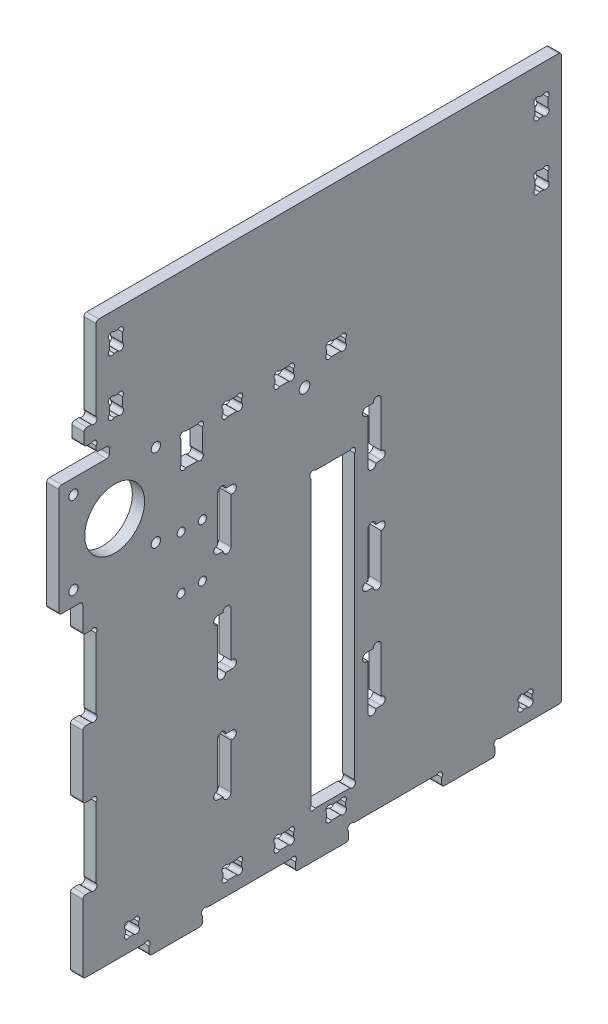
SolidWorks part; units mm, degrees
material "Acrylic (Medium-high impact)"
ref_plane "Front Plane" through (0, 0, 0) normal (0, 0, 1) x (1, 0, 0)
ref_plane "Top Plane" through (0, 0, 0) normal (0, 1, 0) x (1, 0, 0)
ref_plane "Right Plane" through (0, 0, 0) normal (1, 0, 0) x (0, 0, -1)
sketch "Sketch21" plane through (0, 0, 0) normal (1, 0, 0) x (0, 0, -1)
  line L0 (-68, 106) -> (107, 106)
  line L1 (107, 106) -> (107, -106)
  line L2 (107, -106) -> (82, -106)
  line L3 (-45.5, 53.5) -> (-76.5, 53.5) construction
  line L4 (-76.5, 53.5) -> (-76.5, 22.5) construction
  line L5 (-76.5, 22.5) -> (-45.5, 22.5) construction
  line L6 (-13.25, -101) -> (18.75, -101) construction
  line L7 (-20.25, -101) -> (-20.25, -96)
  line L8 (-82, 59) -> (-63, 59)
  line L9 (-48, -106) -> (-48, -111)
  line L10 (-68, 73) -> (-68, 106)
  line L11 (-68, 63) -> (-68, 67)
  line L12 (-73, -106) -> (-48, -106)
  line L13 (-48, -111) -> (-28, -111)
  line L14 (-13.25, -96) -> (-20.25, -96)
  line L15 (-13.25, -101) -> (-13.25, -96)
  line L16 (-13.25, -101) -> (-20.25, -101)
  line L17 (18.75, -101) -> (25.75, -101)
  line L18 (-45.5, 22.5) -> (-45.5, 53.5) construction
  line L19 (-45.5, 53.5) -> (-76.5, 22.5) construction
  line L20 (-57, -96) -> (-52, -96)
  line L21 (-57, -96) -> (-57, -101)
  line L22 (-57, -101) -> (-52, -101)
  line L23 (-52, -96) -> (-52, -101)
  line L24 (91, -96) -> (96, -96)
  line L25 (91, -96) -> (91, -101)
  line L26 (-28, -111) -> (-28, -106)
  line L27 (82, -106) -> (82, -111)
  line L28 (82, -111) -> (62, -111)
  line L29 (62, -111) -> (62, -106)
  line L30 (-48, -106) -> (-119, -106) construction
  line L31 (-20.25, 52.5) -> (25.75, 52.5) construction
  line L32 (62, -106) -> (27, -106)
  line L33 (-0.75, -96) -> (6.25, -96)
  line L34 (29.25, -94) -> (12.75, -94)
  line L35 (29.25, -94) -> (29.25, 16)
  line L36 (29.25, 36) -> (12.75, 36) construction
  line L37 (12.75, -94) -> (12.75, 16)
  line L38 (18.75, -101) -> (18.75, -96)
  line L39 (18.75, -96) -> (25.75, -96)
  line L40 (25.75, -101) -> (25.75, -96)
  line L41 (-0.75, -96) -> (-0.75, -101)
  line L42 (-0.75, -101) -> (6.25, -101)
  line L43 (6.25, -96) -> (6.25, -101)
  line L44 (-0.75, 55) -> (6.25, 55)
  line L45 (-0.75, 55) -> (-0.75, 50)
  line L46 (-0.75, 50) -> (6.25, 50)
  line L47 (6.25, 55) -> (6.25, 50)
  line L48 (102, 92) -> (97, 92) construction
  line L49 (7, -106) -> (-28, -106)
  line L50 (91, -101) -> (96, -101)
  line L51 (7, -106) -> (7, -111)
  line L52 (7, -111) -> (27, -111)
  line L53 (27, -106) -> (27, -111)
  line L54 (96, -96) -> (96, -101)
  line L55 (97, 68) -> (102, 68) construction
  line L56 (-68, 63) -> (-63, 63)
  line L57 (-63, 59) -> (-63, 63)
  line L58 (29.25, 16) -> (12.75, 16)
  line L59 (-63, 99) -> (-58, 99)
  line L60 (-20.25, 55) -> (-13.25, 55)
  line L61 (-20.25, 55) -> (-20.25, 50)
  line L62 (-20.25, 50) -> (-13.25, 50)
  line L63 (-13.25, 55) -> (-13.25, 50)
  line L64 (18.75, 55) -> (25.75, 55)
  line L65 (18.75, 55) -> (18.75, 50)
  line L66 (18.75, 50) -> (25.75, 50)
  line L67 (25.75, 55) -> (25.75, 50)
  line L68 (-68, 73) -> (-72.5, 73)
  line L69 (-73, 6) -> (-68, 6)
  line L70 (-68, 67) -> (-72.5, 67)
  line L71 (-72.5, 73) -> (-72.5, 67)
  line L72 (102, 95.5) -> (97, 95.5)
  line L73 (102, 95.5) -> (102, 88.5)
  line L74 (102, 88.5) -> (97, 88.5)
  line L75 (97, 95.5) -> (97, 88.5)
  line L76 (97, 71.5) -> (102, 71.5)
  line L77 (97, 71.5) -> (97, 64.5)
  line L78 (97, 64.5) -> (102, 64.5)
  line L79 (102, 71.5) -> (102, 64.5)
  line L80 (-63, 99) -> (-63, 92)
  line L81 (2.75, -101) -> (2.75, 123.1045) construction
  line L82 (-73, -106) -> (-73, -79)
  line L83 (22.25, -98.5) -> (-16.75, -98.5) construction
  line L84 (-73, 17) -> (-82, 17)
  line L85 (-82, 17) -> (-82, 59)
  line L86 (-68, 6) -> (-68, -24)
  line L87 (-68, -24) -> (-73, -24)
  line L88 (-73, -49) -> (-68, -49)
  line L89 (-68, -49) -> (-68, -79)
  line L90 (-68, -79) -> (-73, -79)
  line L91 (-68, -9) -> (-73, -9) construction
  line L92 (-73, 6) -> (-73, 17)
  line L93 (-73, -49) -> (-73, -24)
  line L94 (-63, 92) -> (-58, 92)
  line L95 (-58, 99) -> (-58, 92)
  line L96 (-63, 78) -> (-58, 78)
  line L97 (-63, 78) -> (-63, 71)
  line L98 (-63, 71) -> (-58, 71)
  line L99 (-58, 78) -> (-58, 71)
  line L104 (29.25, 16) -> (29.25, 36) construction
  line L106 (12.75, 36) -> (12.75, 16) construction
  circle A0 centre (-16.75, -98.5) radius 2 construction
  circle A1 centre (-16.75, 52.5) radius 2 construction
  circle A2 centre (-45.5, 53.5) radius 1.75
  circle A3 centre (-61, 38) radius 11.25
  circle A4 centre (-76.5, 22.5) radius 1.75
  circle A5 centre (2.75, 52.5) radius 2 construction
  circle A6 centre (22.25, 52.5) radius 2 construction
  circle A7 centre (10.4, 45) radius 2
  circle A8 centre (-76.5, 53.5) radius 1.75
  circle A9 centre (-45.5, 22.5) radius 1.75
  circle A23 centre (2.75, -98.5) radius 2 construction
  circle A35 centre (22.25, -98.5) radius 2 construction
  circle A36 centre (-16.75, -98.5) radius 2 construction
  point P57 (76.5, 13)
  dimension "D1" = 3.5
  dimension "D8" = 22.5
  dimension "D9" = 180
  dimension "D12" = 42
  dimension "D17" = 5
  dimension "D20" = 34.5
  dimension "D34" = 90
  dimension "D37" = 4.5
  dimension "D39" = 30
  dimension "D45" = 5
  dimension "D47" = 7
  dimension "D13" = 21
  dimension "D48" = 12
  dimension "D50" = 104.25
  dimension "D31" = 5
  dimension "D19" = 5
  dimension "D32" = 33
  dimension "D56" = 39
  dimension "D57" = 5
  dimension "D36" = 6
  dimension "D51" = 39
  dimension "D46" = 7
  dimension "D52" = 25
  dimension "D69" = 5
  dimension "D35" = 5
  dimension "D49" = 4
  dimension "D75" = 4
  dimension "D2" = 212
  dimension "D3" = 226
  dimension "D6" = 31
  dimension "D7" = 31
  dimension "D10" = 14
  dimension "D11" = 9
  dimension "D14" = 106
  dimension "D15" = 10
  dimension "D16" = 107
  dimension "D18" = 7
  dimension "D21" = 16
  dimension "D22" = 16.5
  dimension "D23" = 10
  dimension "D24" = 70
  dimension "D25" = 168
  dimension "D26" = 68
  dimension "D27" = 30.5
  dimension "D28" = 119
  dimension "D29" = 175
  dimension "D30" = 5
  dimension "D33" = 47
  dimension "D38" = 115
  dimension "D40" = 5
  dimension "D41" = 20
  dimension "D42" = 4
  dimension "D43" = 25
  dimension "D44" = 30
  dimension "D53" = 10
  dimension "D54" = 7
  dimension "D55" = 51
  dimension "D58" = 32
  dimension "D59" = 14
  dimension "D60" = 5
  dimension "D61" = 5
  dimension "D62" = 10.5
  dimension "D63" = 5
  dimension "D64" = 7
  dimension "D65" = 5
  dimension "D66" = 14
  dimension "D67" = 7
  dimension "D68" = 7
  dimension "D70" = 5
  dimension "D74" = 20
  dimension "D76" = 7.65
  dimension "D77" = 7.5
extrude "Boss-Extrude4" add sketch "Sketch21" along normal blind 4.6
sketch "Sketch25" plane through (4.6, 0, 0) normal (1, 0, 0) x (0, 0, -1)
  line L0 (27, -106) -> (62, -106) construction
  line L1 (34.25, 27) -> (39.25, 27)
  line L2 (34.25, 27) -> (34.25, 7)
  line L3 (34.25, 7) -> (39.25, 7)
  line L4 (39.25, 27) -> (39.25, 7)
  line L5 (34.25, -13) -> (39.25, -13)
  line L6 (34.25, -13) -> (34.25, -33)
  line L7 (34.25, -33) -> (39.25, -33)
  line L8 (39.25, -13) -> (39.25, -33)
  line L9 (34.25, -53) -> (39.25, -53)
  line L10 (34.25, -53) -> (34.25, -73)
  line L11 (34.25, -73) -> (39.25, -73)
  line L12 (39.25, -53) -> (39.25, -73)
  line L13 (29.25, -94) -> (29.25, 16) construction
  line L14 (12.75, 16) -> (12.75, -94) construction
  line L15 (-17.25, 27) -> (-22.25, 27)
  line L16 (-17.25, 27) -> (-17.25, 7)
  line L17 (-17.25, 7) -> (-22.25, 7)
  line L18 (-22.25, 27) -> (-22.25, 7)
  line L19 (-17.25, -13) -> (-22.25, -13)
  line L20 (-17.25, -13) -> (-17.25, -33)
  line L21 (-17.25, -33) -> (-22.25, -33)
  line L22 (-22.25, -13) -> (-22.25, -33)
  line L23 (-17.25, -53) -> (-22.25, -53)
  line L24 (-17.25, -53) -> (-17.25, -73)
  line L25 (-17.25, -73) -> (-22.25, -73)
  line L26 (-22.25, -53) -> (-22.25, -73)
  point P12 (44.5, -106)
  dimension "D1" = 20
  dimension "D2" = 20
  dimension "D3" = 20
  dimension "D4" = 5
  dimension "D5" = 33
  dimension "D6" = 5
  dimension "D7" = 30
extrude "Cut-Extrude6" cut sketch "Sketch25" against normal through all
fillet "Fillet1" radius 1 22 edges at (2.3, 106, -107) (2.3, -106, -107) (2.3, -111, -82) (2.3, -111, -62) (2.3, -111, -27) (2.3, -111, -7) (2.3, -111, 28) (2.3, -111, 48) (2.3, 59, 82) (2.3, 106, 68) (2.3, 73, 72.5) (2.3, 59, 63) (2.3, 63, 63) (2.3, 63, 68) (2.3, 67, 72.5) (2.3, 17, 73) (2.3, 17, 82) (2.3, 6, 73) (2.3, -24, 73) (2.3, -106, 73) (2.3, -79, 73) (2.3, -49, 73)
sketch "Sketch27" plane through (4.6, 0, 0) normal (1, 0, 0) x (0, 0, -1)
  line L0 (-68.8839, 73) -> (-68.8839, 73.8839) construction
  line L1 (-68, 73) -> (-71.5, 73) construction
  line L2 (-68.8839, 73.8839) -> (-68, 73.8839) construction
  line L6 (-68, 105) -> (-68, 73) construction
  line L7 (-72.5, 70) -> (-70.5, 70) construction
  line L8 (-72.5, 72) -> (-72.5, 68) construction
  line L9 (-68, 5.1161) -> (-68.8839, 5.1161) construction
  line L10 (-68.8839, 5.1161) -> (-68.8839, 6) construction
  line L11 (-72, 6) -> (-68, 6) construction
  line L12 (-48, -106.8839) -> (-48.8839, -106.8839) construction
  line L14 (-68, 6) -> (-68, -24) construction
  line L16 (-68, -9) -> (-71.6635, -9) construction
  line L17 (-48, -106) -> (-48, -110) construction
  line L18 (-48.8839, -106.8839) -> (-48.8839, -106) construction
  line L19 (-72, -106) -> (-48, -106) construction
  line L20 (-73, -36.5) -> (-70.5, -36.5) construction
  line L21 (-73, -25) -> (-73, -48) construction
  line L25 (-68, -64) -> (-73.7241, -64) construction
  line L26 (-68, -49) -> (-68, -79) construction
  line L34 (-47, -111) -> (-29, -111) construction
  line L36 (-38, -111) -> (-38, -107.4796) construction
  line L40 (-10.5, -106) -> (-10.5, -111) construction
  line L41 (-28, -106) -> (7, -106) construction
  line L42 (17, -111) -> (17, -106) construction
  line L43 (8, -111) -> (26, -111) construction
  line L44 (44.5, -106) -> (44.5, -111) construction
  line L45 (27, -106) -> (62, -106) construction
  line L46 (72, -111) -> (72, -105.0403) construction
  line L47 (63, -111) -> (81, -111) construction
  circle A0 centre (-68.8839, 73.8839) radius 1.25
  circle A1 centre (-68.8839, 66.1161) radius 1.25
  circle A2 centre (-68.8839, 5.1161) radius 1.25
  circle A3 centre (-68.8839, -23.1161) radius 1.25
  circle A4 centre (-68.8839, -49.8839) radius 1.25
  circle A5 centre (-68.8839, -78.1161) radius 1.25
  circle A6 centre (-48.8839, -106.8839) radius 1.25
  circle A7 centre (-27.1161, -106.8839) radius 1.25
  circle A8 centre (6.1161, -106.8839) radius 1.25
  circle A9 centre (27.8839, -106.8839) radius 1.25
  circle A10 centre (61.1161, -106.8839) radius 1.25
  circle A11 centre (82.8839, -106.8839) radius 1.25
  dimension "D1" = 2.5
  dimension "D2" = 2.5
  dimension "D3" = 2.5
extrude "Cut-Extrude8" cut sketch "Sketch27" against normal through all
sketch "Sketch28" plane through (0, 0, 0) normal (-1, 0, 0) x (0, 0, 1)
  line L0 (43.75, 53.5) -> (43.75, 58.6524) construction
  line L1 (28, 53.1514) -> (36, 53.1514)
  line L2 (28, 53.1514) -> (28, 41.1514)
  line L3 (28, 41.1514) -> (36, 41.1514)
  line L4 (36, 53.1514) -> (36, 41.1514)
  line L7 (20.25, 55) -> (20.25, 50) construction
  circle A0 centre (45.5, 53.5) radius 1.75 construction
  dimension "D3" = 7.75
  dimension "D1" = 8
  dimension "D2" = 12
  dimension "D4" = 7.75
  dimension "D5" = 0.3486
extrude "Cut-Extrude9" cut sketch "Sketch28" against normal through all
sketch "Sketch26" plane through (4.6, 0, 0) normal (1, 0, 0) x (0, 0, -1)
  line L0 (94.6597, 80) -> (104.8986, 80) construction
  line L1 (102, 71.5) -> (97, 71.5) construction
  line L2 (97, 88.5) -> (102, 88.5) construction
  line L3 (97, 94.6161) -> (97.8839, 94.6161) construction
  line L4 (97, 95.5) -> (97, 88.5) construction
  line L5 (97.8839, 94.6161) -> (97.8839, 95.5) construction
  line L6 (102, 95.5) -> (97, 95.5) construction
  line L7 (97, 92) -> (99.744, 92) construction
  line L8 (99.5, 95.5) -> (99.5, 93.0517) construction
  line L9 (95.1161, -96.8839) -> (96, -96.8839) construction
  line L10 (96, -101) -> (96, -96) construction
  line L11 (95.1161, -96.8839) -> (95.1161, -96) construction
  line L12 (96, -96) -> (91, -96) construction
  line L13 (93.5, -96) -> (93.5, -98.2166) construction
  line L14 (96, -98.5) -> (94.7368, -98.5) construction
  line L15 (24.8661, -96.8839) -> (25.75, -96.8839) construction
  line L16 (25.75, -101) -> (25.75, -96) construction
  line L17 (24.8661, -96.8839) -> (24.8661, -96) construction
  line L18 (25.75, -96) -> (18.75, -96) construction
  line L19 (25.75, -98.5) -> (23.6476, -98.5) construction
  line L20 (22.25, -96) -> (22.25, -97.5874) construction
  line L21 (-56.1161, -96) -> (-56.1161, -96.8839) construction
  line L22 (12.75, 15.1161) -> (13.6339, 15.1161) construction
  line L23 (12.75, 16) -> (12.75, -94) construction
  line L24 (13.6339, 15.1161) -> (13.6339, 16) construction
  line L25 (-36, 47.1514) -> (-28, 47.1514) construction
  line L26 (12.75, 16) -> (12.75, -94) construction
  line L27 (12.75, -39) -> (18.3074, -39) construction
  line L28 (-60.5, 99) -> (-60.5, 95.5) construction
  line L29 (-58, 99) -> (-63, 99) construction
  line L30 (-52, -96) -> (-57, -96) construction
  line L31 (-56.1161, -96.8839) -> (-57, -96.8839) construction
  line L32 (-57, -96) -> (-57, -101) construction
  line L33 (-54.5, -96) -> (-54.5, -97.8284) construction
  line L34 (-52, -98.5) -> (-53.6161, -98.5) construction
  line L35 (-52, -101) -> (-52, -96) construction
  line L36 (-60.5, 95.5) -> (-63, 95.5) construction
  line L37 (-63, 99) -> (-63, 92) construction
  line L38 (-62.1161, 99) -> (-62.1161, 98.1161) construction
  line L39 (-62.1161, 98.1161) -> (-63, 98.1161) construction
  line L40 (-64.3381, 85) -> (-53.6161, 85) construction
  line L41 (-63, 92) -> (-58, 92) construction
  line L42 (-58, 78) -> (-63, 78) construction
  line L43 (29.25, 16) -> (12.75, 16) construction
  line L44 (21, 16) -> (21, 13.2431) construction
  line L45 (-36, 41.1514) -> (-36, 53.1514) construction
  line L46 (-28, 53.1514) -> (-28, 41.1514) construction
  line L47 (-32, 53.1514) -> (-32, 41.1514) construction
  line L48 (-36, 53.1514) -> (-28, 53.1514) construction
  line L49 (-28, 41.1514) -> (-36, 41.1514) construction
  line L59 (18.75, -96) -> (18.75, -101) construction
  line L63 (12.5, -94.4003) -> (12.5, -102.9529) construction
  line L64 (-7, -93.6654) -> (-7, -102.9529) construction
  line L65 (6.25, -101) -> (6.25, -96) construction
  line L84 (-13.25, -101) -> (-13.25, -96) construction
  line L85 (-0.75, -96) -> (-0.75, -101) construction
  line L97 (39.25, -71.5) -> (38.75, -71.5) construction
  line L98 (39.25, -73) -> (38.75, -73)
  line L99 (39.25, -70) -> (38.75, -70)
  line L100 (33.75, -54.5) -> (34.25, -54.5) construction
  line L101 (33.75, -53) -> (34.25, -53)
  line L102 (33.75, -56) -> (34.25, -56)
  line L103 (37.75, -53) -> (37.75, -53.5) construction
  line L104 (39.25, -53) -> (39.25, -53.5)
  line L105 (36.25, -53) -> (36.25, -53.5)
  line L106 (35.75, -72.5) -> (35.75, -73) construction
  line L107 (37.25, -72.5) -> (37.25, -73)
  line L108 (34.25, -72.5) -> (34.25, -73)
  line L109 (34.25, -53) -> (34.25, -73) construction
  line L110 (34.25, -73) -> (39.25, -73) construction
  line L111 (39.25, -73) -> (39.25, -53) construction
  line L112 (39.25, -53) -> (34.25, -53) construction
  line L120 (31.423, -43) -> (41.4874, -43) construction
  line L121 (31.423, -3) -> (43.2095, -3) construction
  line L122 (8.5, 43.6339) -> (8.5, -81.0138) construction
  line L123 (34.25, -33) -> (39.25, -33) construction
  line L124 (39.25, -14.5) -> (38.75, -14.5) construction
  line L125 (39.25, -13) -> (38.75, -13)
  line L126 (39.25, -16) -> (38.75, -16)
  line L127 (33.75, -31.5) -> (34.25, -31.5) construction
  line L128 (33.75, -33) -> (34.25, -33)
  line L129 (33.75, -30) -> (34.25, -30)
  line L130 (37.75, -33) -> (37.75, -32.5) construction
  line L131 (39.25, -33) -> (39.25, -32.5)
  line L132 (36.25, -33) -> (36.25, -32.5)
  line L133 (35.75, -13.5) -> (35.75, -13) construction
  line L134 (37.25, -13.5) -> (37.25, -13)
  line L135 (34.25, -13.5) -> (34.25, -13)
  line L136 (39.25, -13) -> (34.25, -13) construction
  line L137 (34.25, 7) -> (39.25, 7) construction
  line L138 (39.25, 8.5) -> (38.75, 8.5) construction
  line L139 (39.25, 7) -> (38.75, 7)
  line L140 (39.25, 10) -> (38.75, 10)
  line L141 (33.75, 25.5) -> (34.25, 25.5) construction
  line L142 (33.75, 27) -> (34.25, 27)
  line L143 (33.75, 24) -> (34.25, 24)
  line L144 (37.75, 27) -> (37.75, 26.5) construction
  line L145 (39.25, 27) -> (39.25, 26.5)
  line L146 (36.25, 27) -> (36.25, 26.5)
  line L147 (35.75, 7.5) -> (35.75, 7) construction
  line L148 (37.25, 7.5) -> (37.25, 7)
  line L149 (34.25, 7.5) -> (34.25, 7)
  line L150 (-17.25, -73) -> (-17.25, -53) construction
  line L151 (-22.25, -71.5) -> (-21.75, -71.5) construction
  line L152 (-22.25, -73) -> (-21.75, -73)
  line L153 (-22.25, -70) -> (-21.75, -70)
  line L154 (-16.75, -54.5) -> (-17.25, -54.5) construction
  line L155 (-16.75, -53) -> (-17.25, -53)
  line L156 (-16.75, -56) -> (-17.25, -56)
  line L157 (-20.75, -53) -> (-20.75, -53.5) construction
  line L158 (-22.25, -53) -> (-22.25, -53.5)
  line L159 (-19.25, -53) -> (-19.25, -53.5)
  line L160 (-18.75, -72.5) -> (-18.75, -73) construction
  line L161 (-20.25, -72.5) -> (-20.25, -73)
  line L162 (-17.25, -72.5) -> (-17.25, -73)
  line L163 (-22.25, -14.5) -> (-21.75, -14.5) construction
  line L164 (-22.25, -13) -> (-21.75, -13)
  line L165 (-22.25, -16) -> (-21.75, -16)
  line L166 (-16.75, -31.5) -> (-17.25, -31.5) construction
  line L167 (-16.75, -33) -> (-17.25, -33)
  line L168 (-16.75, -30) -> (-17.25, -30)
  line L169 (-20.75, -33) -> (-20.75, -32.5) construction
  line L170 (-22.25, -33) -> (-22.25, -32.5)
  line L171 (-19.25, -33) -> (-19.25, -32.5)
  line L172 (-18.75, -13.5) -> (-18.75, -13) construction
  line L173 (-20.25, -13.5) -> (-20.25, -13)
  line L174 (-17.25, -13.5) -> (-17.25, -13)
  line L175 (-22.25, 8.5) -> (-21.75, 8.5) construction
  line L176 (-22.25, 7) -> (-21.75, 7)
  line L177 (-22.25, 10) -> (-21.75, 10)
  line L178 (-16.75, 25.5) -> (-17.25, 25.5) construction
  line L179 (-16.75, 27) -> (-17.25, 27)
  line L180 (-16.75, 24) -> (-17.25, 24)
  line L181 (-20.75, 27) -> (-20.75, 26.5) construction
  line L182 (-22.25, 27) -> (-22.25, 26.5)
  line L183 (-19.25, 27) -> (-19.25, 26.5)
  line L184 (-18.75, 7.5) -> (-18.75, 7) construction
  line L185 (-20.25, 7.5) -> (-20.25, 7)
  line L186 (-17.25, 7.5) -> (-17.25, 7)
  line L187 (-40.1176, -23) -> (18.25, -23) construction
  line L208 (6.25, -96) -> (-0.75, -96) construction
  line L209 (-0.75, 50) -> (6.25, 50) construction
  circle A0 centre (97.8839, 94.6161) radius 1.25
  circle A1 centre (101.1161, 94.6161) radius 1.25
  circle A2 centre (101.1161, 89.3839) radius 1.25
  circle A3 centre (97.8839, 89.3839) radius 1.25
  circle A4 centre (95.1161, -96.8839) radius 1.25
  circle A5 centre (95.1161, -100.1161) radius 1.25
  circle A6 centre (24.8661, -100.1161) radius 1.25
  circle A7 centre (24.8661, -96.8839) radius 1.25
  circle A8 centre (5.3661, -100.1161) radius 1.25
  circle A9 centre (5.3661, -96.8839) radius 1.25
  circle A10 centre (-14.1339, -100.1161) radius 1.25
  circle A11 centre (-14.1339, -96.8839) radius 1.25
  circle A12 centre (-56.1161, -96.8839) radius 1.25
  circle A13 centre (-52.8839, -96.8839) radius 1.25
  circle A14 centre (-19.3661, 54.1161) radius 1.25
  circle A15 centre (-19.3661, 50.8839) radius 1.25
  circle A16 centre (0.1339, 54.1161) radius 1.25
  circle A17 centre (0.1339, 50.8839) radius 1.25
  circle A18 centre (19.6339, 54.1161) radius 1.25
  circle A19 centre (19.6339, 50.8839) radius 1.25
  circle A20 centre (97.8839, 65.3839) radius 1.25
  circle A21 centre (101.1161, 65.3839) radius 1.25
  circle A22 centre (101.1161, 70.6161) radius 1.25
  circle A23 centre (97.8839, 70.6161) radius 1.25
  circle A24 centre (91.8839, -96.8839) radius 1.25
  circle A25 centre (91.8839, -100.1161) radius 1.25
  circle A26 centre (19.6339, -96.8839) radius 1.25
  circle A27 centre (19.6339, -100.1161) radius 1.25
  circle A28 centre (0.1339, -96.8839) radius 1.25
  circle A29 centre (0.1339, -100.1161) radius 1.25
  circle A30 centre (-19.3661, -96.8839) radius 1.25
  circle A31 centre (-19.3661, -100.1161) radius 1.25
  circle A32 centre (-56.1161, -100.1161) radius 1.25
  circle A33 centre (-52.8839, -100.1161) radius 1.25
  circle A34 centre (-14.1339, 50.8839) radius 1.25
  circle A35 centre (-14.1339, 54.1161) radius 1.25
  circle A36 centre (5.3661, 50.8839) radius 1.25
  circle A37 centre (5.3661, 54.1161) radius 1.25
  circle A38 centre (24.8661, 50.8839) radius 1.25
  circle A39 centre (24.8661, 54.1161) radius 1.25
  circle A40 centre (13.6339, 15.1161) radius 1.25
  circle A41 centre (28.3661, 15.1161) radius 1.25
  circle A42 centre (28.3661, -93.1161) radius 1.25
  circle A43 centre (13.6339, -93.1161) radius 1.25
  circle A44 centre (-62.1161, 98.1161) radius 1.25
  circle A45 centre (-58.8839, 98.1161) radius 1.25
  circle A46 centre (-101.6339, 54.1161) radius 1.25
  circle A47 centre (-58.8839, 92.8839) radius 1.25
  arc A48 (39.25, -73) -> (39.25, -70) centre (39.25, -71.5) ccw
  arc A49 (38.75, -70) -> (38.75, -73) centre (38.75, -71.5) ccw
  arc A50 (33.75, -53) -> (33.75, -56) centre (33.75, -54.5) ccw
  arc A51 (34.25, -56) -> (34.25, -53) centre (34.25, -54.5) ccw
  arc A52 (39.25, -53) -> (36.25, -53) centre (37.75, -53) ccw
  arc A53 (36.25, -53.5) -> (39.25, -53.5) centre (37.75, -53.5) ccw
  arc A54 (37.25, -72.5) -> (34.25, -72.5) centre (35.75, -72.5) ccw
  arc A55 (34.25, -73) -> (37.25, -73) centre (35.75, -73) ccw
  arc A56 (39.25, -13) -> (39.25, -16) centre (39.25, -14.5) cw
  arc A57 (38.75, -16) -> (38.75, -13) centre (38.75, -14.5) cw
  arc A58 (33.75, -33) -> (33.75, -30) centre (33.75, -31.5) cw
  arc A59 (34.25, -30) -> (34.25, -33) centre (34.25, -31.5) cw
  arc A60 (39.25, -33) -> (36.25, -33) centre (37.75, -33) cw
  arc A61 (36.25, -32.5) -> (39.25, -32.5) centre (37.75, -32.5) cw
  arc A62 (37.25, -13.5) -> (34.25, -13.5) centre (35.75, -13.5) cw
  arc A63 (34.25, -13) -> (37.25, -13) centre (35.75, -13) cw
  arc A64 (39.25, 7) -> (39.25, 10) centre (39.25, 8.5) ccw
  arc A65 (38.75, 10) -> (38.75, 7) centre (38.75, 8.5) ccw
  arc A66 (33.75, 27) -> (33.75, 24) centre (33.75, 25.5) ccw
  arc A67 (34.25, 24) -> (34.25, 27) centre (34.25, 25.5) ccw
  arc A68 (39.25, 27) -> (36.25, 27) centre (37.75, 27) ccw
  arc A69 (36.25, 26.5) -> (39.25, 26.5) centre (37.75, 26.5) ccw
  arc A70 (37.25, 7.5) -> (34.25, 7.5) centre (35.75, 7.5) ccw
  arc A71 (34.25, 7) -> (37.25, 7) centre (35.75, 7) ccw
  arc A72 (-22.25, -73) -> (-22.25, -70) centre (-22.25, -71.5) cw
  arc A73 (-21.75, -70) -> (-21.75, -73) centre (-21.75, -71.5) cw
  arc A74 (-16.75, -53) -> (-16.75, -56) centre (-16.75, -54.5) cw
  arc A75 (-17.25, -56) -> (-17.25, -53) centre (-17.25, -54.5) cw
  arc A76 (-22.25, -53) -> (-19.25, -53) centre (-20.75, -53) cw
  arc A77 (-19.25, -53.5) -> (-22.25, -53.5) centre (-20.75, -53.5) cw
  arc A78 (-20.25, -72.5) -> (-17.25, -72.5) centre (-18.75, -72.5) cw
  arc A79 (-17.25, -73) -> (-20.25, -73) centre (-18.75, -73) cw
  arc A80 (-22.25, -13) -> (-22.25, -16) centre (-22.25, -14.5) ccw
  arc A81 (-21.75, -16) -> (-21.75, -13) centre (-21.75, -14.5) ccw
  arc A82 (-16.75, -33) -> (-16.75, -30) centre (-16.75, -31.5) ccw
  arc A83 (-17.25, -30) -> (-17.25, -33) centre (-17.25, -31.5) ccw
  arc A84 (-22.25, -33) -> (-19.25, -33) centre (-20.75, -33) ccw
  arc A85 (-19.25, -32.5) -> (-22.25, -32.5) centre (-20.75, -32.5) ccw
  arc A86 (-20.25, -13.5) -> (-17.25, -13.5) centre (-18.75, -13.5) ccw
  arc A87 (-17.25, -13) -> (-20.25, -13) centre (-18.75, -13) ccw
  arc A88 (-22.25, 7) -> (-22.25, 10) centre (-22.25, 8.5) cw
  arc A89 (-21.75, 10) -> (-21.75, 7) centre (-21.75, 8.5) cw
  arc A90 (-16.75, 27) -> (-16.75, 24) centre (-16.75, 25.5) cw
  arc A91 (-17.25, 24) -> (-17.25, 27) centre (-17.25, 25.5) cw
  arc A92 (-22.25, 27) -> (-19.25, 27) centre (-20.75, 27) cw
  arc A93 (-19.25, 26.5) -> (-22.25, 26.5) centre (-20.75, 26.5) cw
  arc A94 (-20.25, 7.5) -> (-17.25, 7.5) centre (-18.75, 7.5) cw
  arc A95 (-17.25, 7) -> (-20.25, 7) centre (-18.75, 7) cw
  circle A96 centre (-62.1161, 92.8839) radius 1.25
  circle A97 centre (-58.8839, 71.8839) radius 1.25
  circle A98 centre (-62.1161, 71.8839) radius 1.25
  circle A99 centre (-62.1161, 77.1161) radius 1.25
  circle A100 centre (-58.8839, 77.1161) radius 1.25
  circle A101 centre (-35.12, 52.2637) radius 1.25
  circle A102 centre (-35.12, 42.0392) radius 1.25
  circle A103 centre (-28.88, 42.0392) radius 1.25
  circle A104 centre (-28.88, 52.2637) radius 1.25
  point P218 (39, -71.5)
  point P223 (34, -54.5)
  point P230 (37.75, -53.25)
  point P237 (35.75, -72.75)
  point P252 (39, -14.5)
  point P259 (34, -31.5)
  point P266 (37.75, -32.75)
  point P273 (35.75, -13.25)
  point P284 (39, 8.5)
  point P291 (34, 25.5)
  point P298 (37.75, 26.75)
  point P305 (35.75, 7.25)
  point P314 (-22, -71.5)
  point P321 (-17, -54.5)
  point P328 (-20.75, -53.25)
  point P335 (-18.75, -72.75)
  point P342 (-22, -14.5)
  point P349 (-17, -31.5)
  point P356 (-20.75, -32.75)
  point P363 (-18.75, -13.25)
  point P370 (-22, 8.5)
  point P377 (-17, 25.5)
  point P384 (-20.75, 26.75)
  point P391 (-18.75, 7.25)
  dimension "D2" = 2.5
  dimension "D4" = 0.88
  dimension "D12" = 1.5
  dimension "D3" = 2.5
  dimension "D11" = 0.5
extrude "Cut-Extrude7" cut sketch "Sketch26" against normal through all
sketch "Sketch29" plane through (0, 0, 0) normal (-1, 0, 0) x (0, 0, 1)
  line L0 (29.76, 41.1514) -> (34.24, 41.1514) construction
  line L1 (24.1376, 21.1514) -> (36, 21.1514) construction
  line L2 (28, 47.1514) -> (28, 1.1514) construction
  line L3 (28, 51.3759) -> (28, 42.9269) construction
  line L4 (36, 42.9269) -> (36, 1.1514) construction
  line L6 (28, 1.1514) -> (36, 1.1514) construction
  circle A0 centre (28, 21.1514) radius 1.5
  circle A1 centre (36, 21.1514) radius 1.5
  circle A2 centre (36, 1.1514) radius 1.5
  circle A3 centre (28, 1.1514) radius 1.5
  point P16 (28, 21.1514)
  dimension "D3" = 3
  dimension "D4" = 3
  dimension "D5" = 3
  dimension "D6" = 3
  dimension "D1" = 20
  dimension "D2" = 20
extrude "Cut-Extrude10" cut sketch "Sketch29" against normal blind 10
